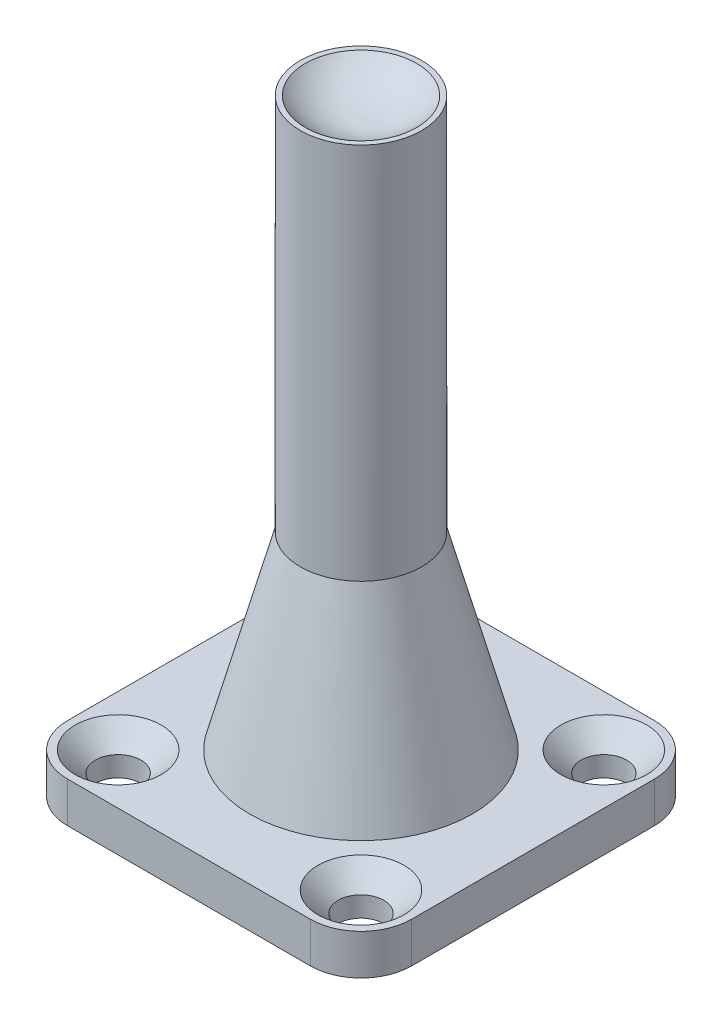
SolidWorks part; units mm, degrees
ref_plane "Спереди" through (0, 0, 0) normal (0, 0, 1) x (1, 0, 0)
ref_plane "Сверху" through (0, 0, 0) normal (0, 1, 0) x (1, 0, 0)
ref_plane "Справа" through (0, 0, 0) normal (1, 0, 0) x (0, 0, -1)
sketch "Эскиз1" plane through (0, 0, 0) normal (0, 1, 0) x (1, 0, 0)
  line L1 (-17, -17) -> (17, -17)
  line L2 (-17, -17) -> (-17, 17)
  line L3 (-17, 17) -> (17, 17)
  line L4 (17, -17) -> (17, 17)
  line L5 (0, 17) -> (0, -17) construction
  line L6 (-17, 0) -> (17, 0) construction
  line L7 (-12, -12) -> (12, -12) construction
  line L8 (-12, -12) -> (-12, 12) construction
  line L9 (-12, 12) -> (12, 12) construction
  line L10 (12, -12) -> (12, 12) construction
  line L11 (0, 12) -> (0, -12) construction
  line L12 (-12, 0) -> (12, 0) construction
  circle A0 centre (-12, 12) radius 2.25
  circle A1 centre (12, 12) radius 2.25
  circle A2 centre (12, -12) radius 2.25
  circle A3 centre (-12, -12) radius 2.25
  point P0 (0, 0)
  point P4 (0, 0)
  dimension "D5" = 4.5
  dimension "D1" = 34
  dimension "D3" = 24
  dimension "D4" = 24
extrude "Бобышка-Вытянуть1" add sketch "Эскиз1" along normal blind 4
fillet "Скругление1" radius 5 4 edges at (17, 2, 17) (-17, 2, -17) (17, 2, -17) (-17, 2, 17)
sketch "Эскиз2" plane through (0, 4, 0) normal (0, 1, 0) x (1, 0, 0)
  circle A0 centre (0, 0) radius 6
  dimension "D1" = 12
extrude "Бобышка-Вытянуть2" add sketch "Эскиз2" along normal blind 56
ref_plane "Плоскость1" through (0, 0, 0) normal (0, 0, 1) x (1, 0, 0)
sketch "Эскиз7" plane through (0, 0, 0) normal (0, 0, 1) x (1, 0, 0)
  line L0 (0, 82.4047) -> (0, 58) construction
  line L1 (0, 58) -> (9.0963, 58) construction
  line L2 (6, 60) -> (-6, 60) construction
  line L3 (5.5, 60) -> (0, 60)
  line L4 (0, 60) -> (0, 58)
  arc A0 (0, 58) -> (0.0893, 58) centre (0.0447, 58) ccw
  arc A1 (5.5, 60) -> (0, 58) centre (0.6855, 64.6775) cw
  dimension "D1" = 2
  dimension "D2" = 5.5
revolve "Вырез-Повернуть3" cut sketch "Эскиз7" angle 360 about L0
chamfer "Фаска1" distance 5 angle 75 1 edges at (0, 4, 6)
sketch "Эскиз5" plane through (0, 0, 0) normal (0, -1, 0) x (1, 0, 0)
  line L1 (-16.5147, -16.1651) -> (16.5147, -16.1651)
  line L2 (-16.5147, -16.1651) -> (-16.5147, 16.1651)
  line L3 (-16.5147, 16.1651) -> (16.5147, 16.1651)
  line L4 (16.5147, -16.1651) -> (16.5147, 16.1651)
  line L5 (0, 16.1651) -> (0, -16.1651) construction
  line L6 (-16.5147, 0) -> (16.5147, 0) construction
  point P0 (0, 0)
extrude "Вырез-Вытянуть2" [suppressed] cut sketch "Эскиз5" against normal blind 70
chamfer "Фаска2" distance 2 angle 45 4 edges at (-12, 4, 14.25) (12, 4, 14.25) (-12, 4, -9.75) (12, 4, -9.75)
